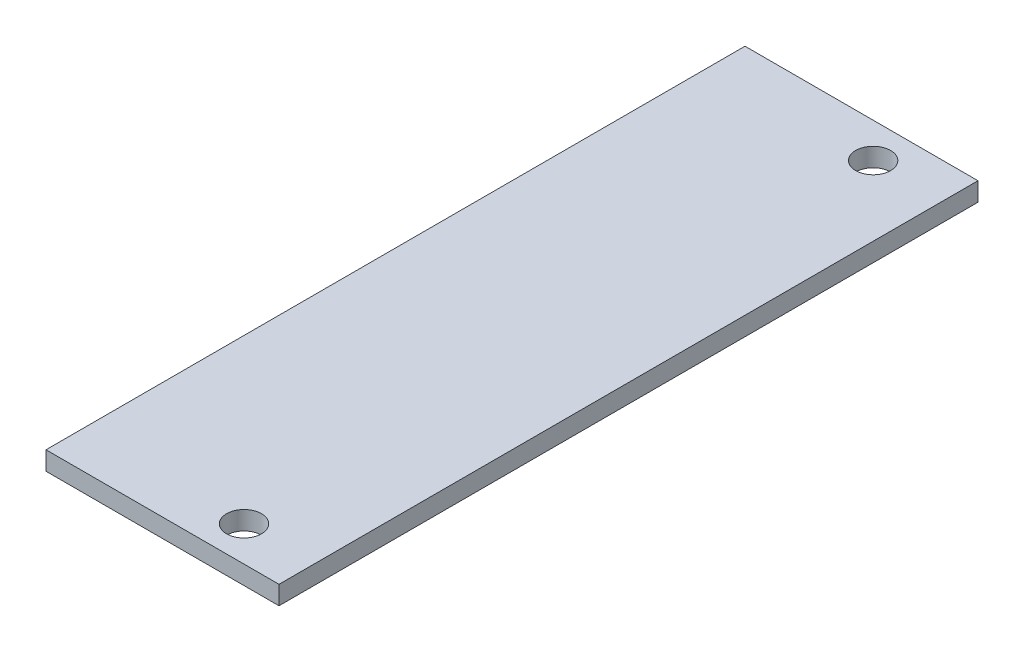
SolidWorks part; units mm, degrees
ref_plane "Front Plane" through (0, 0, 0) normal (0, 0, 1) x (1, 0, 0)
ref_plane "Top Plane" through (0, 0, 0) normal (0, 1, 0) x (1, 0, 0)
ref_plane "Right Plane" through (0, 0, 0) normal (1, 0, 0) x (0, 0, -1)
sketch "Sketch1" plane through (0, 0, 0) normal (0, 1, 0) x (1, 0, 0)
  line L1 (0, 0) -> (20, 0)
  line L2 (0, 0) -> (0, 60)
  line L3 (0, 60) -> (20, 60)
  line L4 (20, 0) -> (20, 60)
  circle A0 centre (14, 3) radius 1.5
  circle A1 centre (14, 57) radius 1.5
  dimension "D3" = 3
  dimension "D4" = 3
  dimension "D1" = 20
  dimension "D2" = 60
  dimension "D5" = 6
  dimension "D6" = 6
  dimension "D7" = 3
  dimension "D8" = 3
extrude "pcb_board" add sketch "Sketch1" along normal blind 1.6
